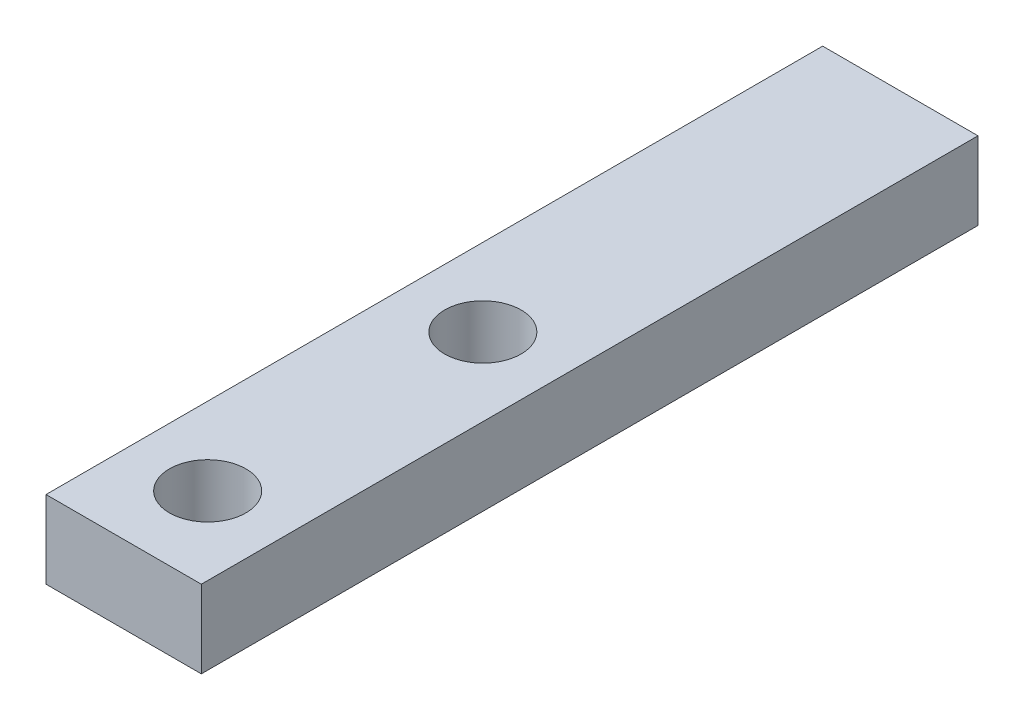
SolidWorks part; units mm, degrees
ref_plane "Front Plane" through (0, 0, 0) normal (0, 0, 1) x (1, 0, 0)
ref_plane "Top Plane" through (0, 0, 0) normal (0, 1, 0) x (1, 0, 0)
ref_plane "Right Plane" through (0, 0, 0) normal (1, 0, 0) x (0, 0, -1)
sketch "Sketch1" plane through (0, 0, 0) normal (0, 1, 0) x (1, 0, 0)
  line L1 (0, 0) -> (5.08, 0)
  line L2 (0, 0) -> (0, 25.4)
  line L3 (0, 25.4) -> (5.08, 25.4)
  line L4 (5.08, 0) -> (5.08, 25.4)
  circle A0 centre (2.54, 2.7472) radius 1.25
  circle A1 centre (2.54, 11.7472) radius 1.25
  dimension "D1" = 2.5
  dimension "D2" = 2.5
  dimension "D3" = 9
  dimension "D6" = 2.54
  dimension "D4" = 25.4
  dimension "D5" = 5.08
extrude "Boss-Extrude1" add sketch "Sketch1" along normal blind 2.54
